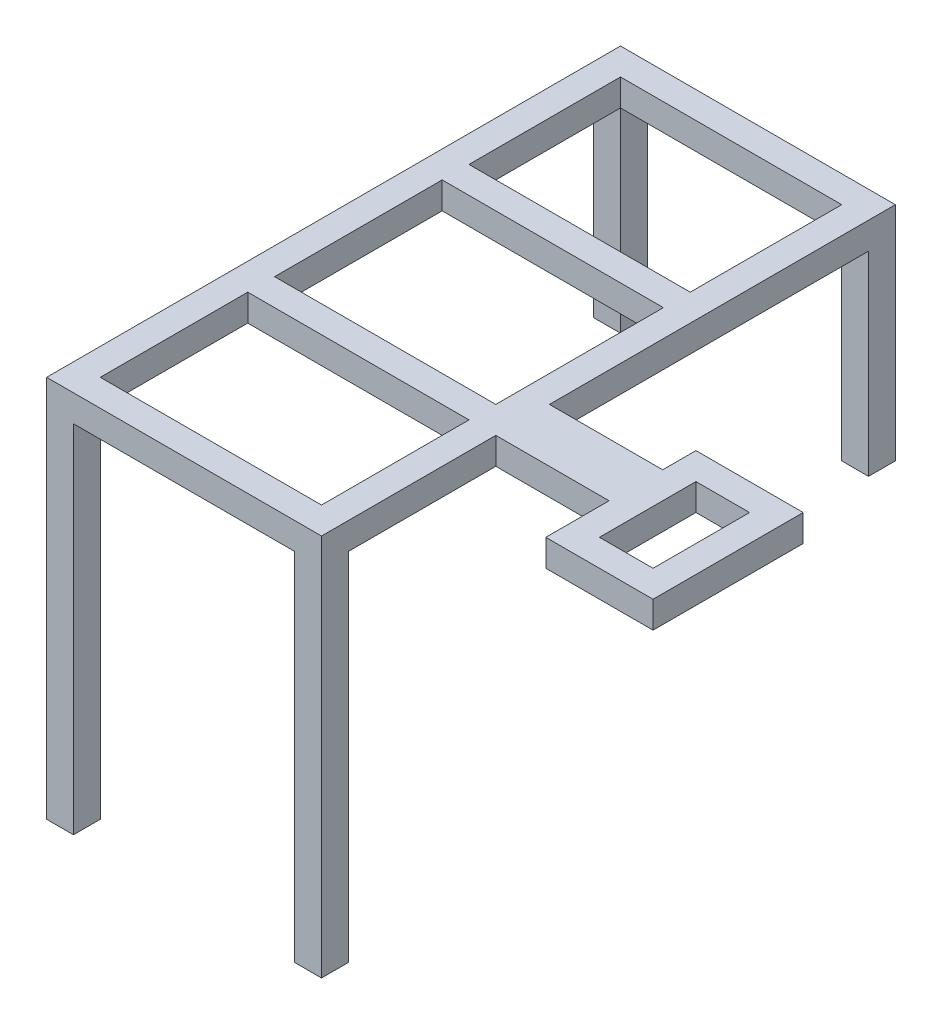
SolidWorks part; units mm, degrees
ref_plane "Front Plane" through (0, 0, 0) normal (0, 0, 1) x (1, 0, 0)
ref_plane "Top Plane" through (0, 0, 0) normal (0, 1, 0) x (1, 0, 0)
ref_plane "Right Plane" through (0, 0, 0) normal (1, 0, 0) x (0, 0, -1)
sketch "Sketch2" plane through (0, 0, 0) normal (0, 1, 0) x (1, 0, 0)
  line L0 (-25.4, 25.4) -> (-25.4, -184.15)
  line L1 (0, 0) -> (209.55, 0)
  line L2 (0, 0) -> (0, -158.75)
  line L3 (0, -158.75) -> (209.55, -158.75)
  line L4 (209.55, 0) -> (209.55, -158.75)
  line L5 (-25.4, -184.15) -> (234.95, -184.15)
  line L6 (234.95, 25.4) -> (234.95, -184.15)
  line L7 (-25.4, 25.4) -> (234.95, 25.4)
  line L8 (234.95, -184.15) -> (342.2396, -184.15)
  line L9 (234.95, -133.35) -> (342.2396, -133.35)
  line L10 (342.2396, -133.35) -> (342.2396, -184.15)
  line L11 (367.6396, -127.254) -> (367.6396, -218.694)
  line L12 (342.2396, -101.854) -> (443.8396, -101.854)
  line L13 (342.2396, -101.854) -> (342.2396, -244.094)
  line L14 (342.2396, -244.094) -> (443.8396, -244.094)
  line L15 (443.8396, -101.854) -> (443.8396, -244.094)
  line L16 (367.6396, -218.694) -> (418.4396, -218.694)
  line L17 (418.4396, -127.254) -> (418.4396, -218.694)
  line L18 (367.6396, -127.254) -> (418.4396, -127.254)
  point P20 (238.0662, -158.75)
  point P21 (0, 0)
  point P22 (0, 0)
  point P23 (0, 0)
  point P24 (0, 0)
  point P25 (0, 0)
  point P26 (0, 0)
  dimension "D1" = 209.55
  dimension "D2" = 158.75
  dimension "D4" = 107.2896
  dimension "D5" = 101.6
  dimension "D6" = 142.24
  dimension "D8" = 59.944
  dimension "D9" = 50.8
  dimension "D3" = 25.4
  dimension "D7" = 25.4
extrude "Boss-Extrude1" add sketch "Sketch2" along normal blind 25.4 contours L7 L0 L5 L6 L1 L4 L3 L2 | L15 L12 L10 L13 L14 L11 L18 L17 L16 | L10 L9 L6 L8
sketch "Sketch3" plane through (0, 25.4, 0) normal (0, 1, 0) x (1, 0, 0)
  line L0 (-25.4, 194.31) -> (-25.4, -349.25)
  line L1 (-25.4, 25.4) -> (234.95, 25.4) construction
  line L2 (-25.4, 194.31) -> (234.95, 194.31)
  line L3 (234.95, 194.31) -> (234.95, -349.25)
  line L4 (234.95, -349.25) -> (-25.4, -349.25)
  line L5 (234.95, 25.4) -> (234.95, -133.35) construction
  line L6 (-25.4, 25.4) -> (-25.4, -184.15) construction
  line L7 (0, 168.91) -> (209.55, 168.91)
  line L8 (209.55, 168.91) -> (209.55, -323.85)
  line L9 (209.55, -323.85) -> (0, -323.85)
  line L10 (0, 168.91) -> (0, -323.85)
  dimension "D1" = 543.56
  dimension "D2" = 168.91
  dimension "D3" = 25.4
extrude "Boss-Extrude2" add sketch "Sketch3" against normal blind 25.4
sketch "Sketch4" plane through (0, 0, 0) normal (0, -1, 0) x (1, 0, 0)
  line L1 (-25.4, -194.31) -> (0, -194.31)
  line L2 (-25.4, -194.31) -> (-25.4, -168.91)
  line L3 (-25.4, -168.91) -> (0, -168.91)
  line L4 (0, -194.31) -> (0, -168.91)
  line L5 (234.95, -194.31) -> (209.55, -194.31)
  line L6 (234.95, -194.31) -> (234.95, -168.91)
  line L7 (234.95, -168.91) -> (209.55, -168.91)
  line L8 (209.55, -194.31) -> (209.55, -168.91)
extrude "Boss-Extrude3" add sketch "Sketch4" along normal blind 184.785
sketch "Sketch5" plane through (0, 0, 0) normal (0, -1, 0) x (1, 0, 0)
  line L1 (-25.4, 349.25) -> (0, 349.25)
  line L2 (-25.4, 349.25) -> (-25.4, 323.85)
  line L3 (-25.4, 323.85) -> (0, 323.85)
  line L4 (0, 349.25) -> (0, 323.85)
  line L5 (234.95, 349.25) -> (209.55, 349.25)
  line L6 (234.95, 349.25) -> (234.95, 323.85)
  line L7 (234.95, 323.85) -> (209.55, 323.85)
  line L8 (209.55, 349.25) -> (209.55, 323.85)
extrude "Boss-Extrude4" add sketch "Sketch5" along normal blind 337.185
